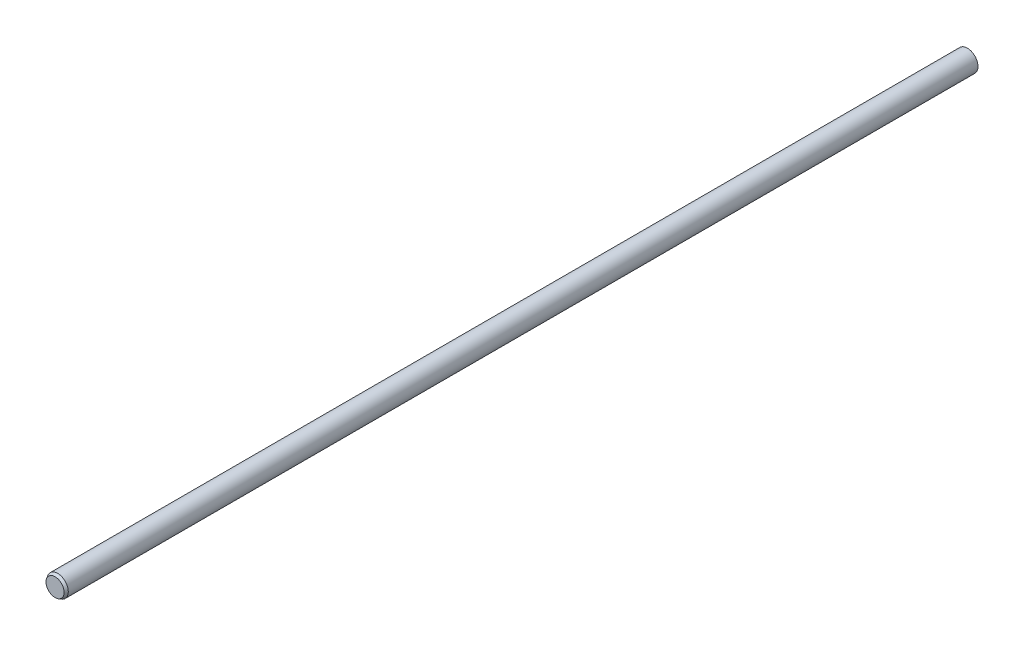
SolidWorks part; units mm, degrees
material "1060 Alloy"
ref_plane "Front Plane" through (0, 0, 0) normal (0, 0, 1) x (1, 0, 0)
ref_plane "Top Plane" through (0, 0, 0) normal (0, 1, 0) x (1, 0, 0)
ref_plane "Right Plane" through (0, 0, 0) normal (1, 0, 0) x (0, 0, -1)
sketch "Sketch1" plane through (0, 0, 0) normal (0, 0, 1) x (1, 0, 0)
  circle A0 centre (0, 0) radius 4
extrude "Boss-Extrude1" add sketch "Sketch1" along normal blind 345
chamfer "Chamfer1" distance 1 angle 30 2 edges at (4, 0, 345) (4, 0, 0)
